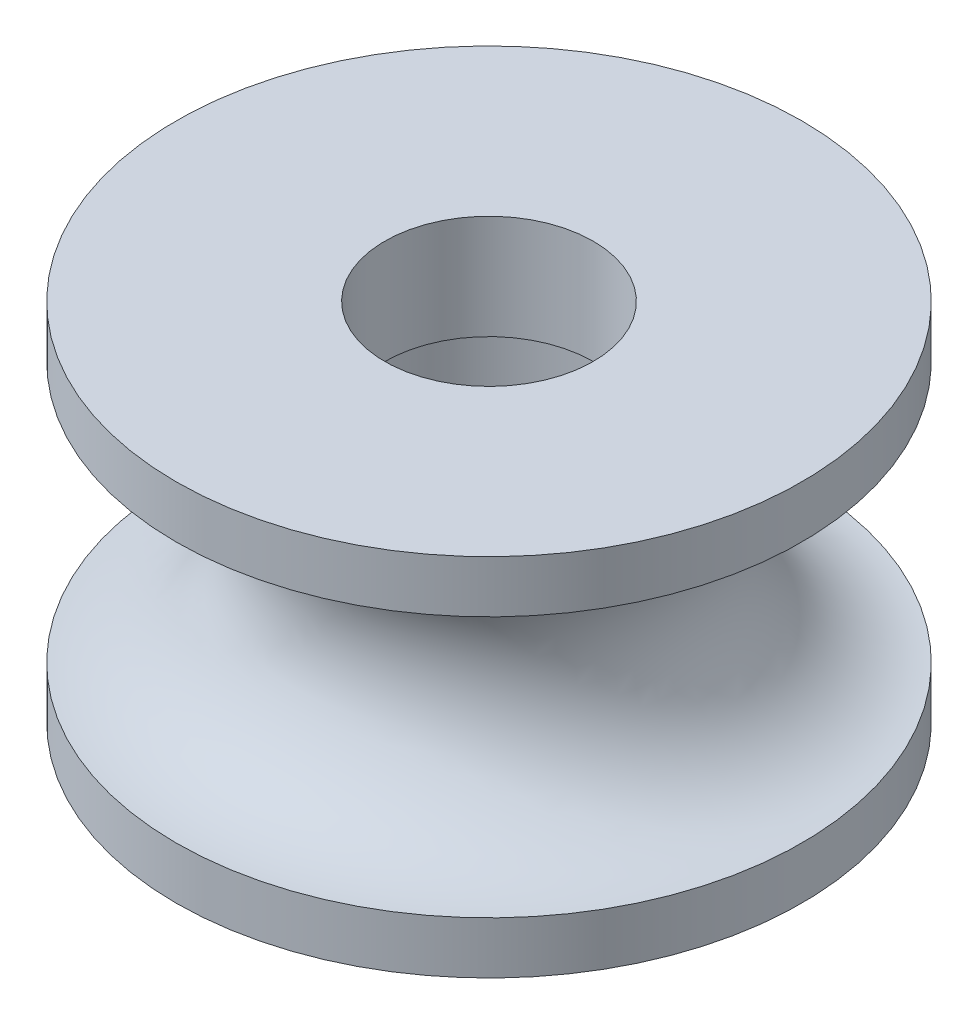
SolidWorks part; units mm, degrees
ref_plane "前视基准面" through (0, 0, 0) normal (0, 0, 1) x (1, 0, 0)
ref_plane "上视基准面" through (0, 0, 0) normal (0, 1, 0) x (1, 0, 0)
ref_plane "右视基准面" through (0, 0, 0) normal (1, 0, 0) x (0, 0, -1)
sketch "草图6" plane through (0, 0, 0) normal (0, 0, 1) x (1, 0, 0)
  line L0 (0, 0) -> (0, 17.1768) construction
sketch "草图7" plane through (0, 0, 0) normal (0, 0, 1) x (1, 0, 0)
  line L1 (-5, 4) -> (-5, -4)
  line L3 (0, -200000) -> (0, 200017.1768) construction
  line L4 (0, 0) -> (-53.5124, 0) construction
  line L5 (-12, 5) -> (-12, 0) construction
  line L6 (-12, 0) -> (-12, -5) construction
  line L7 (-12, 0) -> (-12, 5) construction
  line L8 (-12, 5) -> (-12, 7)
  line L9 (-12, 7) -> (-5, 7)
  line L10 (-5, 7) -> (-5, 4)
  line L11 (-12, -5) -> (-12, -7)
  line L12 (-12, -7) -> (-5, -7)
  line L13 (-5, -7) -> (-5, -4)
  circle A0 centre (-12, 0) radius 5 construction
  arc A1 (-12, 5) -> (-12, -5) centre (-12, 0) cw
  point P6 (-5, 0)
  dimension "D1" = 5
  dimension "D2" = 5
  dimension "D3" = 2
  dimension "D4" = 7
  dimension "D5" = 180
  dimension "D6" = 2
revolve "旋转1" add sketch "草图7" angle 360 about L0
sketch "草图8" plane through (0, 0, 0) normal (0, 1, 0) x (1, 0, 0)
  line L0 (0, 12) -> (0, -12) construction
  circle A0 centre (0, 0) radius 12 construction
sketch "草图9" plane through (0, 0, 0) normal (0, 0, 1) x (1, 0, 0)
  line L0 (-5, -7) -> (5, -7) construction
  line L1 (-5, 7) -> (-4, 7)
  line L2 (-5, 7) -> (-5, 3)
  line L3 (-5, -7) -> (-4, -7)
  line L4 (-4, 7) -> (-4, 3)
  line L5 (-5, 3) -> (-4, 3)
  line L6 (-5, -3) -> (-4, -3)
  line L7 (-5, -3) -> (-5, -7)
  line L8 (-4, -3) -> (-4, -7)
  dimension "D1" = 1
  dimension "D2" = 4
  dimension "D3" = 4
revolve "旋转2" add sketch "草图9" angle 360 about L0
sketch "草图10" plane through (0, -7, 0) normal (0, -1, 0) x (1, 0, 0)
  circle A0 centre (0, 0) radius 5.1
  dimension "D1" = 10.2
extrude "切除-拉伸1" cut sketch "草图10" against normal blind 10
